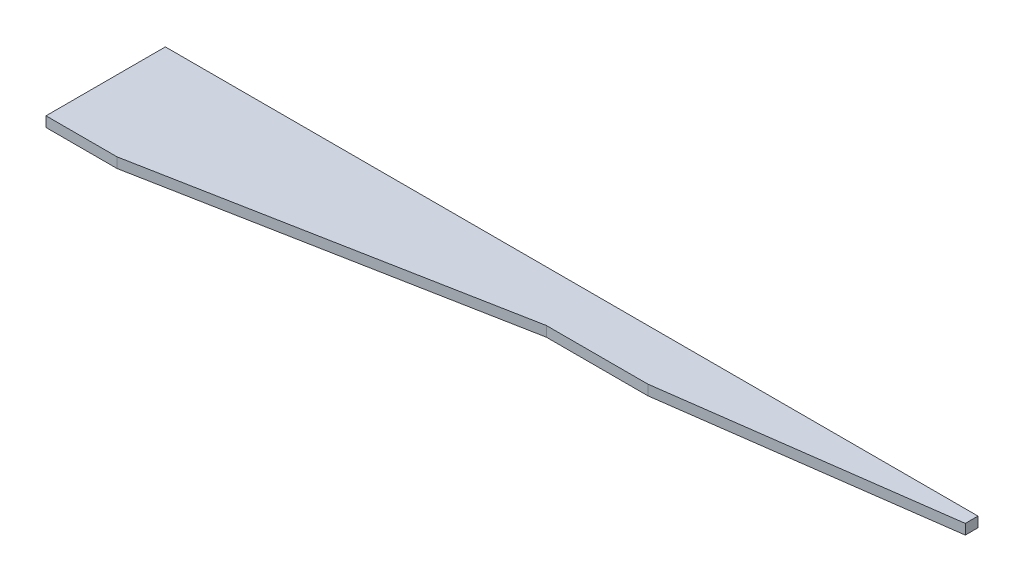
SolidWorks part; units mm, degrees
ref_plane "Front Plane" through (0, 0, 0) normal (0, 0, 1) x (1, 0, 0)
ref_plane "Top Plane" through (0, 0, 0) normal (0, 1, 0) x (1, 0, 0)
ref_plane "Right Plane" through (0, 0, 0) normal (1, 0, 0) x (0, 0, -1)
sketch "Sketch1" plane through (0, 0, 0) normal (0, 1, 0) x (1, 0, 0)
  line L0 (0, 0) -> (0, -47)
  line L1 (0, -47) -> (28, -47)
  line L2 (320, 0) -> (0, 0)
  line L3 (320, 0) -> (320, -5)
  line L4 (28, -47) -> (320, -5) construction
  line L5 (170, -20) -> (210, -20)
  line L6 (170, -20) -> (28, -47)
  line L7 (210, -20) -> (320, -5)
  point P8 (190, -20)
  dimension "D1" = 47
  dimension "D2" = 320
  dimension "D3" = 5
  dimension "D4" = 28
  dimension "D5" = 130
  dimension "D6" = 40
  dimension "D7" = 20
extrude "Boss-Extrude1" add sketch "Sketch1" along normal blind 4
